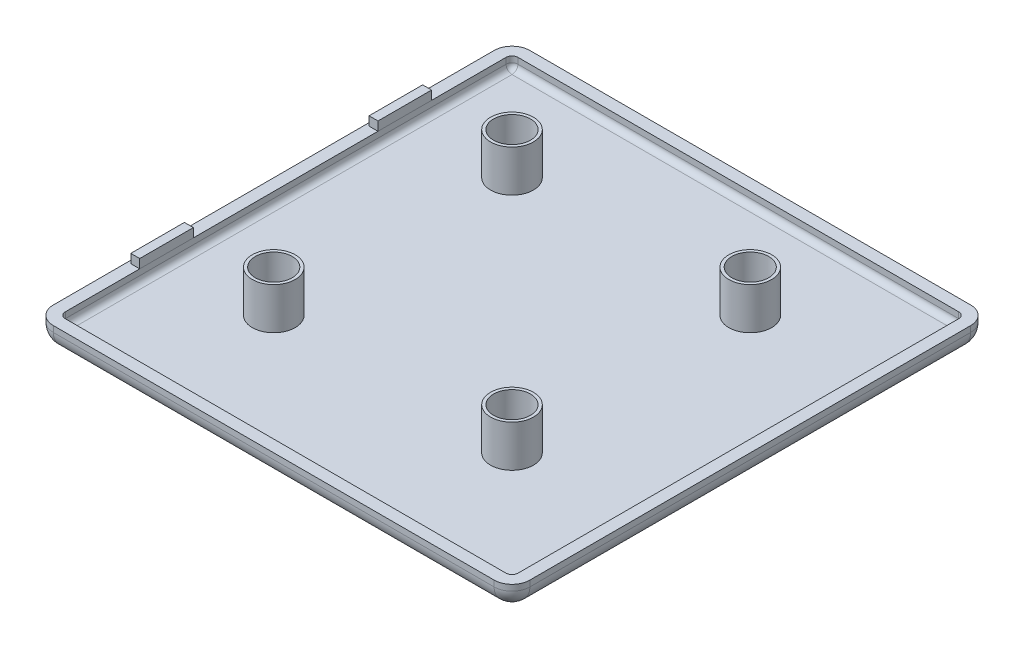
SolidWorks part; units mm, degrees
ref_plane "前视基准面" through (0, 0, 0) normal (0, 0, 1) x (1, 0, 0)
ref_plane "上视基准面" through (0, 0, 0) normal (0, 1, 0) x (1, 0, 0)
ref_plane "右视基准面" through (0, 0, 0) normal (1, 0, 0) x (0, 0, -1)
sketch "草图1" plane through (0, 0, 0) normal (0, 1, 0) x (1, 0, 0)
  line B0 (2.1213, -0.8787) -> (76.1213, -0.8787)
  line B1 (79.1213, 2.1213) -> (79.1213, 76.1213)
  line B2 (76.1213, 79.1213) -> (2.1213, 79.1213)
  line B3 (-0.8787, 76.1213) -> (-0.8787, 2.1213)
  arc B4 (76.1213, -0.8787) -> (79.1213, 2.1213) centre (76.1213, 2.1213) ccw
  arc B5 (79.1213, 76.1213) -> (76.1213, 79.1213) centre (76.1213, 76.1213) ccw
  arc B6 (2.1213, 79.1213) -> (-0.8787, 76.1213) centre (2.1213, 76.1213) ccw
  arc B7 (-0.8787, 2.1213) -> (2.1213, -0.8787) centre (2.1213, 2.1213) ccw
sketch_block_instance "A$C64264E3A-1"
sketch_block "A$C64264E3A"
extrude "凸台-拉伸1" add sketch "草图1" along normal blind 4
fillet "圆角1" radius 3 8 edges at (0, 0, 0) (-0.8787, 0, -39.1213) (0, 0, -78.2426) (39.1213, 0, -79.1213) (78.2426, 0, -78.2426) (79.1213, 0, -39.1213) (78.2426, 0, 0) (39.1213, 0, 0.8787)
shell "抽壳1" thickness 2
sketch "草图3" plane through (0, 4, 0) normal (0, 1, 0) x (1, 0, 0)
  line L0 (1.1213, 39.1213) -> (77.1213, 39.1213) construction
  line L1 (1.1213, 76.1213) -> (1.1213, 2.1213) construction
  line L2 (77.1213, 2.1213) -> (77.1213, 76.1213) construction
  line L3 (39.1213, 77.1213) -> (39.1213, 39.1213) construction
  line L4 (76.1213, 77.1213) -> (2.1213, 77.1213) construction
  circle A0 centre (19.1213, 59.1213) radius 3.6
  circle A1 centre (19.1213, 59.1213) radius 3.1
  circle A2 centre (59.1213, 59.1213) radius 3.6
  circle A3 centre (59.1213, 59.1213) radius 3.1
  circle A4 centre (59.1213, 19.1213) radius 3.6
  circle A5 centre (59.1213, 19.1213) radius 3.1
  circle A6 centre (19.1213, 19.1213) radius 3.6
  circle A7 centre (19.1213, 19.1213) radius 3.1
  point P29 (39.1213, 39.1213)
  dimension "D1" = 7.2
  dimension "D2" = 20
  dimension "D3" = 20
  dimension "D4" = 0.5
  dimension "D5" = 4
extrude "凸台-拉伸2" add sketch "草图3" along normal blind 7 separate body
sketch "草图4" plane through (0, 4, 0) normal (0, 1, 0) x (1, 0, 0)
  line L0 (1.1213, 76.1213) -> (1.1213, 2.1213) construction
  line L1 (1.1213, 63.6213) -> (-0.3787, 63.6213)
  line L2 (1.1213, 63.6213) -> (1.1213, 54.6213)
  line L3 (1.1213, 54.6213) -> (-0.3787, 54.6213)
  line L4 (-0.3787, 63.6213) -> (-0.3787, 54.6213)
  line L5 (76.1213, 39.1213) -> (38.2446, 39.1213) construction
  line L6 (76.1213, 76.1213) -> (76.1213, 2.1213) construction
  line L7 (-0.3787, 14.6213) -> (-0.3787, 23.6213)
  line L8 (1.1213, 23.6213) -> (-0.3787, 23.6213)
  line L9 (1.1213, 14.6213) -> (1.1213, 23.6213)
  line L10 (1.1213, 14.6213) -> (-0.3787, 14.6213)
  circle A0 centre (19.1213, 59.1213) radius 3.1 construction
  circle A1 centre (19.1213, 59.1213) radius 3.6 construction
  dimension "D1" = 1.5
  dimension "D2" = 4.5
  dimension "D3" = 4.5
extrude "凸台-拉伸3" add sketch "草图4" along normal blind 1.5 separate body
